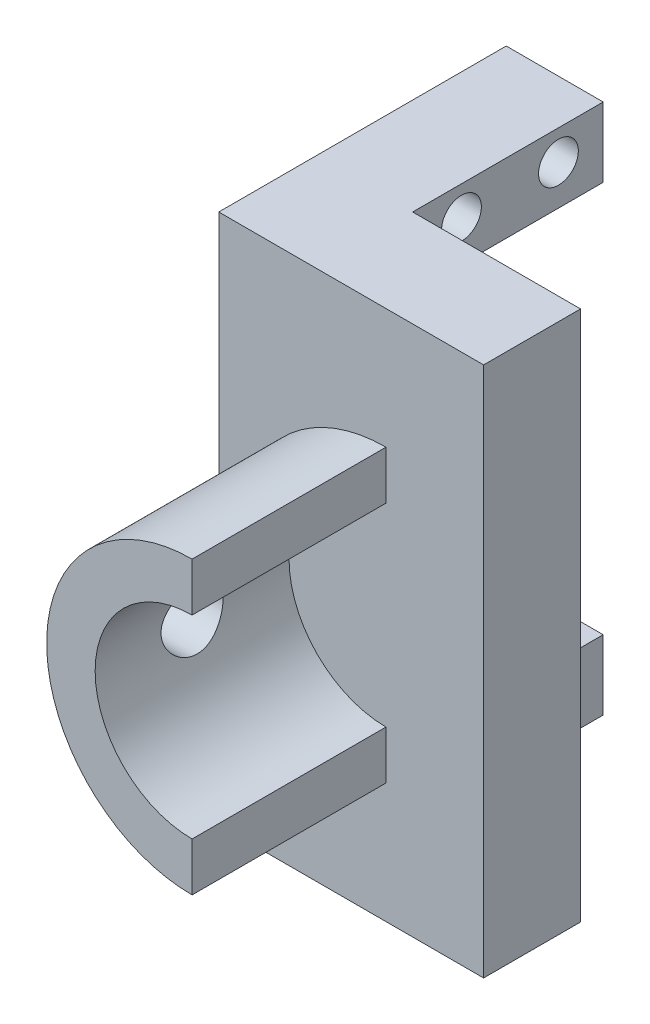
SolidWorks part; units mm, degrees
ref_plane "Front Plane" through (0, 0, 0) normal (0, 0, 1) x (1, 0, 0)
ref_plane "Top Plane" through (0, 0, 0) normal (0, 1, 0) x (1, 0, 0)
ref_plane "Right Plane" through (0, 0, 0) normal (1, 0, 0) x (0, 0, -1)
sketch "Sketch1" plane through (0, 0, 0) normal (0, 0, 1) x (1, 0, 0)
  line L0 (0, 14.859) -> (0, 9.906)
  line L1 (0, -9.906) -> (0, -14.859)
  arc A0 (0, 9.906) -> (0, -9.906) centre (0, 0) ccw
  arc A1 (0, 14.859) -> (0, -14.859) centre (0, 0) ccw
  dimension "D1" = 19.812
  dimension "D2" = 29.718
extrude "Boss-Extrude1" add sketch "Sketch1" along normal blind 19.812
sketch "Sketch2" plane through (0, 0, 0) normal (1, 0, 0) x (0, 0, -1)
  line L0 (0, 0) -> (-19.812, 0) construction
  line L1 (-19.812, 9.906) -> (-19.812, -9.906) construction
  line L2 (-19.812, 14.859) -> (0, 14.859) construction
  line L3 (-9.906, 14.859) -> (-9.906, -14.859) construction
  line L4 (-19.812, -14.859) -> (0, -14.859) construction
  circle A0 centre (-9.906, 0) radius 3.175
  dimension "D1" = 6.35
extrude "Cut-Extrude2" cut sketch "Sketch2" against normal through all
sketch "Sketch3" plane through (0, 0, 0) normal (0, 0, -1) x (-1, 0, 0)
  line L1 (17.0879, -27.1272) -> (-17.0878, -27.1272)
  line L2 (17.0879, -27.1272) -> (17.0879, 27.1272)
  line L3 (17.0879, 27.1272) -> (-17.0878, 27.1272)
  line L4 (-17.0878, -27.1272) -> (-17.0878, 27.1272)
  line L5 (17.0879, -27.1272) -> (-17.0878, 27.1272) construction
  line L6 (17.0879, 27.1272) -> (-17.0878, -27.1272) construction
  point P0 (0, 0)
  dimension "D1" = 34.1757
  dimension "D2" = 54.2544
extrude "Boss-Extrude2" add sketch "Sketch3" along normal blind 9.906
sketch "Sketch4" plane through (0, 0, -9.906) normal (0, 0, -1) x (-1, 0, 0)
  line L0 (0, 0) -> (17.0878, 0) construction
  line L1 (17.0879, -27.1272) -> (7.1819, -27.1272)
  line L2 (17.0879, -27.1272) -> (17.0879, -20.0152)
  line L3 (17.0879, -20.0152) -> (7.1819, -20.0152)
  line L4 (7.1819, -27.1272) -> (7.1819, -20.0152)
  line L5 (17.0879, -27.1272) -> (17.0879, 27.1272) construction
  line L6 (17.0879, 20.0152) -> (7.1819, 20.0152)
  line L7 (7.1819, 27.1272) -> (7.1819, 20.0152)
  line L8 (17.0879, 27.1272) -> (7.1819, 27.1272)
  line L9 (17.0879, 27.1272) -> (17.0879, 20.0152)
  dimension "D1" = 9.906
  dimension "D2" = 7.112
extrude "Boss-Extrude3" add sketch "Sketch4" along normal blind 19.4691
sketch "Sketch5" plane through (-17.0879, 0, 0) normal (-1, 0, 0) x (0, 0, 1)
  line L0 (-29.3751, 27.1272) -> (0, 27.1272) construction
  line L1 (-29.3751, 20.0152) -> (-29.3751, 27.1272) construction
  line L2 (0, 0) -> (-34.8834, 0) construction
  circle A0 centre (-24.8031, 24.0792) radius 2.032
  circle A1 centre (-14.8971, 24.0792) radius 2.032
  circle A2 centre (-14.8971, -24.0792) radius 2.032
  circle A3 centre (-24.8031, -24.0792) radius 2.032
  dimension "D1" = 4.064
  dimension "D4" = 4.064
  dimension "D2" = 3.048
  dimension "D3" = 4.572
  dimension "D5" = 14.478
extrude "Cut-Extrude3" cut sketch "Sketch5" against normal through all
sketch "Sketch6" plane through (0, 0, -9.906) normal (0, 0, -1) x (-1, 0, 0)
  line L0 (-17.0878, -27.1272) -> (7.1819, -27.1272) construction
  line L1 (-17.0878, 27.1272) -> (-9.9758, 27.1272)
  line L2 (-17.0878, 27.1272) -> (-17.0878, -27.1272)
  line L3 (-17.0878, -27.1272) -> (-9.9758, -27.1272)
  line L4 (-9.9758, 27.1272) -> (-9.9758, -27.1272)
  dimension "D1" = 7.112
extrude "Cut-Extrude4" cut sketch "Sketch6" against normal through all
